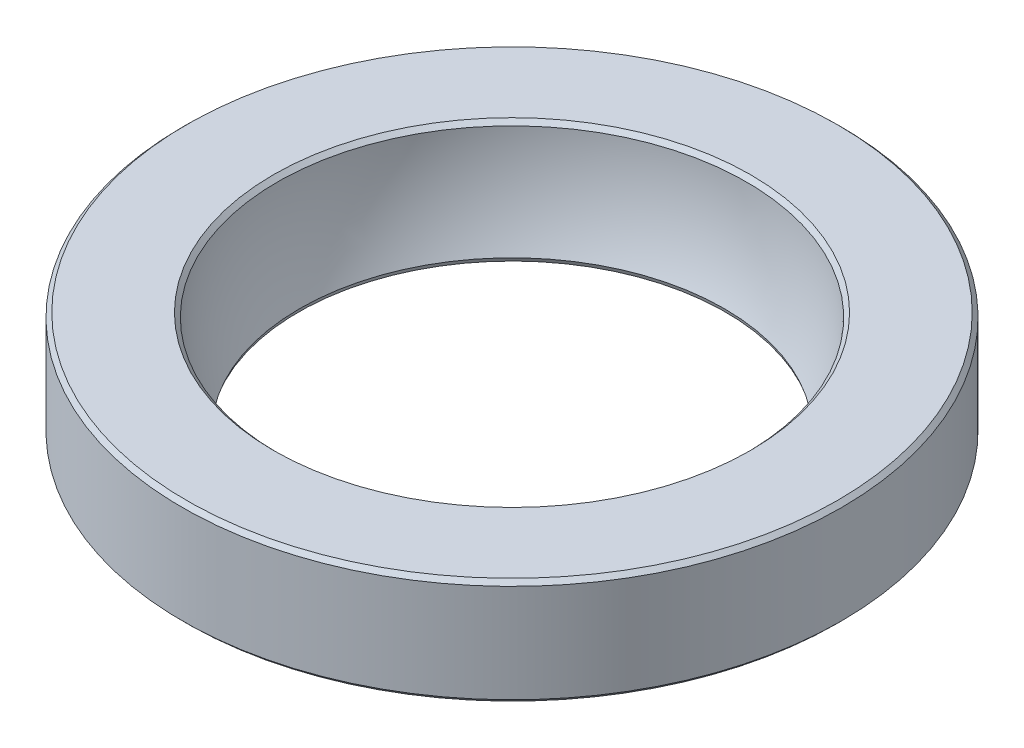
SolidWorks part; units mm, degrees
ref_plane "Front Plane" through (0, 0, 0) normal (0, 0, 1) x (1, 0, 0)
ref_plane "Top Plane" through (0, 0, 0) normal (0, 1, 0) x (1, 0, 0)
ref_plane "Right Plane" through (0, 0, 0) normal (1, 0, 0) x (0, 0, -1)
sketch "Sketch1" plane through (0, 0, 0) normal (0, 0, 1) x (1, 0, 0)
  line L0 (0, 6) -> (0, -6)
  line L1 (0, -6) -> (-6.25, -6)
  line L3 (-6.25, 6) -> (0, 6)
  arc A0 (-6.25, -6) -> (-6.25, 6) centre (0.4582, 0) cw
  point P6 (0, 0)
  dimension "D3" = 9
  dimension "D1" = 12
  dimension "D2" = 6.25
sketch "Sketch2" plane through (0, 0, 0) normal (0, 0, 1) x (1, 0, 0)
  line L0 (-7.6649, -3.875) -> (-12, -3.875)
  line L1 (-12, -3.875) -> (-12, 3.875)
  line L2 (-12, 3.875) -> (-7.6649, 3.875)
  line L3 (0, 6) -> (0, -6) construction
  arc A0 (-6.25, 6) -> (-6.25, -6) centre (0.4582, 0) ccw construction
  arc A1 (-7.6649, 3.875) -> (-7.6649, -3.875) centre (0.4582, 0) ccw
  dimension "D1" = 12
  dimension "D2" = 7.75
revolve "Revolve1" add sketch "Sketch2" angle 360 about L0
sketch "Sketch3" plane through (0, 0, 0) normal (0, 0, 1) x (1, 0, 0)
  line L0 (-12, 3.875) -> (-12, -3.875) construction
  line L1 (-12, 0) -> (13.397, 0)
  line L2 (-12, 0) -> (-12, 7.2545)
  line L3 (-12, 7.2545) -> (13.397, 7.2545)
  line L4 (13.397, 0) -> (13.397, 7.2545)
extrude "Cut-Extrude1" cut sketch "Sketch3" against normal through all both and the other way through all
chamfer "Chamfer1" distance 0.15 angle 45 4 edges at (-12, -3.875, 0) (-7.6649, -3.875, 0) (0, 0, -12) (0, 0, -8.5418)
